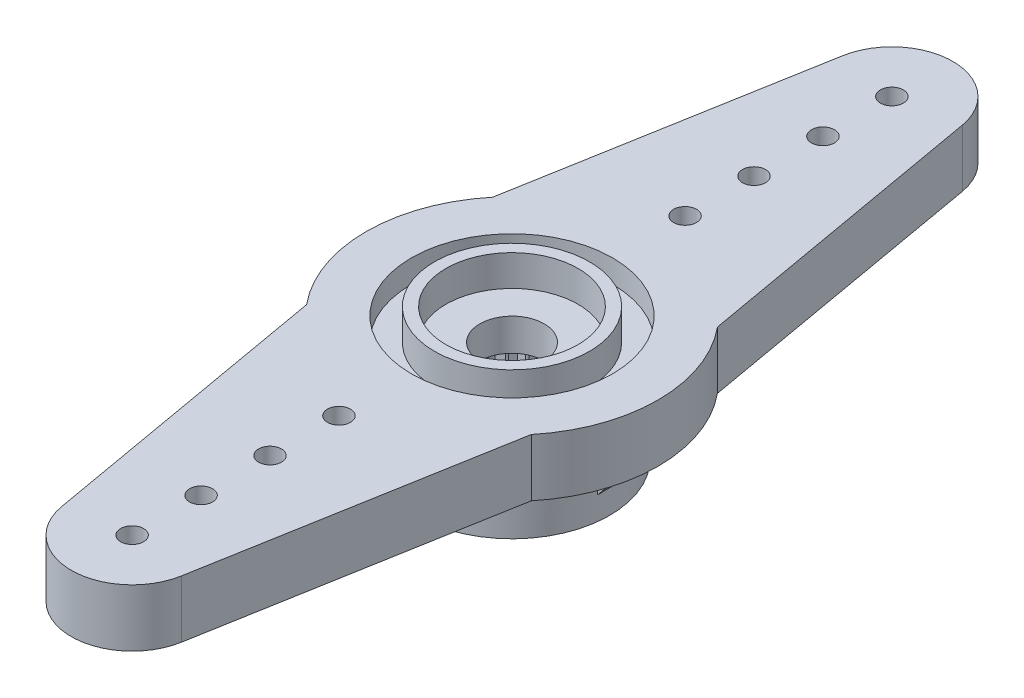
SolidWorks part; units mm, degrees
material "PC High Viscosity"
ref_plane "Front Plane" through (0, 0, 0) normal (0, 0, 1) x (1, 0, 0)
ref_plane "Top Plane" through (0, 0, 0) normal (0, 1, 0) x (1, 0, 0)
ref_plane "Right Plane" through (0, 0, 0) normal (1, 0, 0) x (0, 0, -1)
sketch "BaseS" plane through (0, 0, 0) normal (0, 1, 0) x (1, 0, 0)
  circle A0 centre (0, 0) radius 6.35
  dimension "D1" = 12.7
extrude "BASE" add sketch "BaseS" along normal blind 5.4
sketch "TopBoreS" plane through (0, 5.4, 0) normal (0, 1, 0) x (1, 0, 0)
  circle A0 centre (0, 0) radius 1.4
  dimension "D1" = 2.8
extrude "TOP BORE" cut sketch "TopBoreS" against normal through all
sketch "HornHalfS" plane through (0, 5.4, 0) normal (0, 1, 0) x (1, 0, 0)
  line L0 (0, 0) -> (0, 16.53) construction
  line L1 (-2.6097, 16.9902) -> (-4.8916, 4.049)
  line L2 (0, 19.18) -> (0, 16.53) construction
  line L3 (2.6097, 16.9902) -> (4.8916, 4.049)
  arc A0 (2.6097, 16.9902) -> (-2.6097, 16.9902) centre (0, 16.53) ccw
  arc A1 (4.8916, 4.049) -> (-4.8916, 4.049) centre (0, 0) ccw
  circle A2 centre (0, 0) radius 6.35 construction
  dimension "D1" = 5.3
  dimension "D2" = 19.18
  dimension "D3" = 10
  dimension "D4" = 9.7832
extrude "HORN HALF" add sketch "HornHalfS" against normal blind 2.5
sketch "HornAttachS" plane through (0, 5.4, 0) normal (0, 1, 0) x (1, 0, 0)
  circle A0 centre (0, 16.53) radius 0.5
  dimension "D1" = 1
extrude "HORN ATTACH" cut sketch "HornAttachS" against normal through all
sketch "HA LP RS" plane through (0, 0, 0) normal (0, 1, 0) x (1, 0, 0)
  line L0 (0, 0) -> (0, 16.53) construction
pattern_linear "HA LP" count 4 spacing 3 along (0, 0, 1) of "HORN ATTACH"
mirror "HORN BODIES" about plane through (0, 0, 0) normal (0, 0, 1) of "HA LP", "HORN ATTACH", "HORN HALF"
sketch "ToothS" plane through (0, 0, 0) normal (0, -1, 0) x (1, 0, 0)
  line L0 (0, -2.9) -> (0.2629, -2.5867)
  line L1 (0, -2.9) -> (-0.2629, -2.5867)
  line L2 (0, -2.6) -> (0, -2.9) construction
  line L3 (0, 0) -> (0, -2.6) construction
  arc A0 (-0.2629, -2.5867) -> (0.2629, -2.5867) centre (0, 0) ccw
  dimension "D1" = 5.2
  dimension "D2" = 80
  dimension "D3" = 0.3
extrude "TOOTH" cut sketch "ToothS" against normal blind 3
pattern_circular "TOOTH CP" count 26 over 360 about axis through (0, 0, 0) along (0, 1, 0) of "TOOTH"
sketch "BottomBoreS" plane through (0, 0, 0) normal (0, -1, 0) x (-1, 0, 0)
  circle A0 centre (0, 0) radius 2.6
  arc A1 (0.2629, 2.5867) -> (-0.2629, 2.5867) centre (0, 0) ccw construction
extrude "BOTTOM BORE" cut sketch "BottomBoreS" against normal up to surface (3 mm away) up to face at (-0.6451, 3, 2.6172)
sketch "HoldingShaftS" plane through (0, 0, 0) normal (0, -1, 0) x (1, 0, 0)
  circle A0 centre (0, 0) radius 6.35 construction
  circle A1 centre (0, 0) radius 6.35
  circle A2 centre (0, 0) radius 4.25
  dimension "D1" = 2.1
  dimension "D2" = 8.5
extrude "HOLDING SHAFT" cut sketch "HoldingShaftS" against normal up to surface (2.9 mm away) up to face at (0, 2.9, -13.03)
sketch "RibS" plane through (0, 0, 0) normal (0, 0, 1) x (1, 0, 0)
  line L0 (4.21, 1) -> (5.8043, 2.9)
  line L1 (5.8043, 2.9) -> (4.21, 2.9)
  line L2 (4.21, 1) -> (4.16, 1)
  line L3 (4.16, 1) -> (4.16, 2.9)
  line L4 (4.21, 1) -> (4.21, 2.9) construction
  line L5 (4.16, 2.9) -> (4.21, 2.9)
  line L6 (-4.25, 2.9) -> (4.25, 2.9) construction
  line L7 (4.21, 2.9) -> (4.25, 2.9) construction
  line L8 (4.25, 0) -> (4.25, 2.9) construction
  dimension "D1" = 1.9
  dimension "D2" = 0.05
  dimension "D3" = 40
  dimension "D4" = 0.09
extrude "RIB" add sketch "RibS" along normal mid plane 1
pattern_circular "RIB CP" count 4 over 360 about axis through (0, 0, 0) along (0, 1, 0) of "RIB"
sketch "TopCutS" plane through (0, 5.4, 0) normal (0, 1, 0) x (1, 0, 0)
  circle A0 centre (0, 0) radius 4.375
  arc A1 (4.8916, -4.049) -> (4.8916, 4.049) centre (0, 0) ccw construction
  dimension "D1" = 1.975
  dimension "D2" = 8.75
extrude "TOP CUT" cut sketch "TopCutS" against normal blind 1
sketch "TopPocketCylinderS" plane through (0, 4.4, 0) normal (0, 1, 0) x (1, 0, 0)
  circle A0 centre (0, 0) radius 2.875
  circle A1 centre (0, 0) radius 3.375
  circle A2 centre (0, 0) radius 4.375 construction
  dimension "D2" = 0.5
  dimension "D1" = 1
  dimension "D3" = 6.75
extrude "TOP POCKET CYLINDER" add sketch "TopPocketCylinderS" along normal offset from surface (1.35 mm away) 0.35 up to face at (0, 5.4, 4.375) offset beyond the face yes
sketch "Sketch1" plane through (0, 5.4, 0) normal (0, 1, 0) x (1, 0, 0)
  line L0 (0, 0) -> (0, 7.53)
